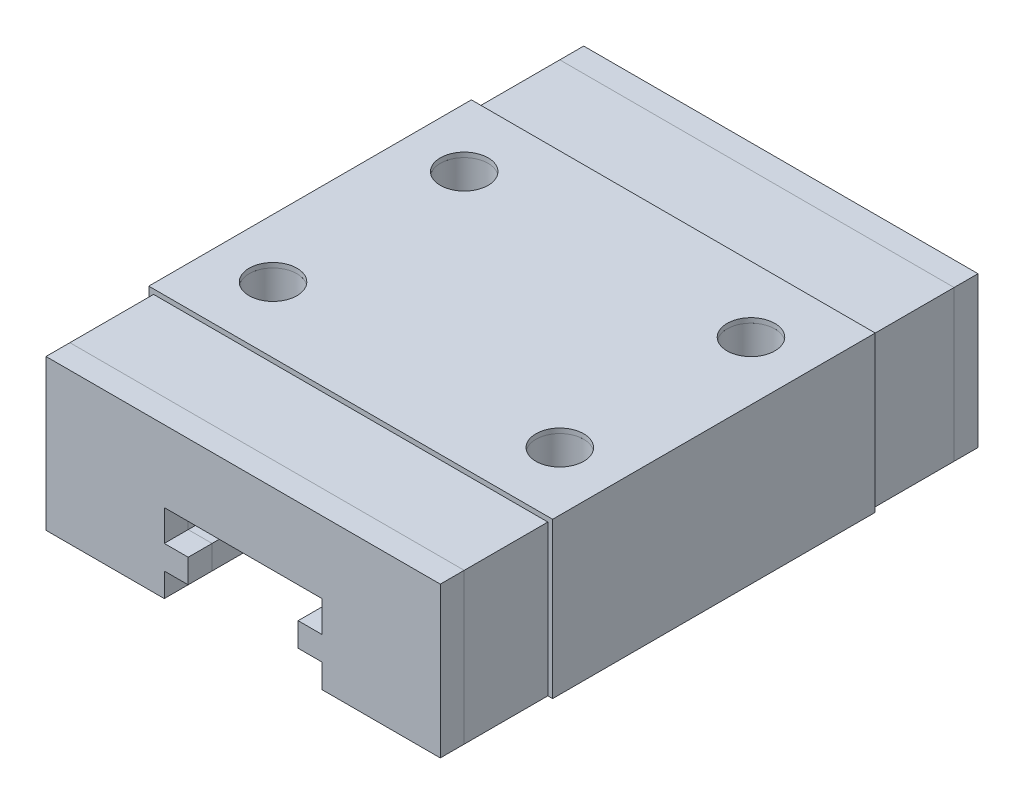
SolidWorks part; units mm, degrees
material "1060 合金"
ref_plane "前视基准面" through (0, 0, 0) normal (0, 0, 1) x (1, 0, 0)
ref_plane "上视基准面" through (0, 0, 0) normal (0, 1, 0) x (1, 0, 0)
ref_plane "右视基准面" through (0, 0, 0) normal (1, 0, 0) x (0, 0, -1)
sketch "草图1" plane through (0, 0, 0) normal (0, 0, 1) x (1, 0, 0)
  line L0 (0, 0) -> (0, 6.3)
  line L1 (0, 6.3) -> (16.5, 6.3)
  line L2 (16.5, 6.3) -> (16.5, 0)
  line L3 (16.5, 0) -> (11.55, 0)
  line L4 (0, 0) -> (4.95, 0)
  line L5 (4.95, 0) -> (4.95, 1)
  line L6 (4.95, 1) -> (5.95, 1)
  line L7 (5.95, 1) -> (5.95, 2)
  line L8 (5.95, 2) -> (4.95, 2)
  line L9 (4.95, 2) -> (4.95, 3.3)
  line L10 (4.95, 3.3) -> (11.55, 3.3)
  line L11 (11.55, 3.3) -> (11.55, 2)
  line L12 (11.55, 2) -> (10.55, 2)
  line L13 (10.55, 2) -> (10.55, 1)
  line L14 (10.55, 1) -> (11.55, 1)
  line L15 (11.55, 1) -> (11.55, 0)
  line L16 (8.25, 6.3) -> (8.25, 0) construction
  dimension "D1" = 16.5
  dimension "D2" = 6.3
  dimension "D3" = 6.6
  dimension "D4" = 3
  dimension "D5" = 1.3
  dimension "D6" = 1
  dimension "D7" = 1
extrude "凸台-拉伸1" add sketch "草图1" along normal blind 1
sketch "草图2" plane through (0, 0, 1) normal (0, 0, 1) x (1, 0, 0)
  line L0 (4.95, 0) -> (4.95, 1)
  line L1 (4.95, 1) -> (5.95, 1)
  line L2 (5.95, 1) -> (5.95, 2)
  line L3 (5.95, 2) -> (4.95, 2)
  line L4 (4.95, 2) -> (4.95, 3.3)
  line L5 (4.95, 3.3) -> (11.55, 3.3)
  line L6 (11.55, 3.3) -> (11.55, 2)
  line L7 (11.55, 2) -> (10.55, 2)
  line L8 (10.55, 2) -> (10.55, 1)
  line L9 (10.55, 1) -> (11.55, 1)
  line L10 (11.55, 1) -> (11.55, 0)
  line L11 (11.55, 0) -> (16.5, 0)
  line L13 (16.5, 0) -> (16.5, 6.3)
  line L14 (16.5, 6.3) -> (0, 6.3)
  line L15 (0, 6.3) -> (0, 0)
  line L16 (0, 0) -> (4.95, 0) construction
  line L17 (0, 0) -> (4.95, 0)
extrude "凸台-拉伸2" add sketch "草图2" along normal blind 20.5 separate body
sketch "草图3" plane through (0, 0, 21.5) normal (0, 0, 1) x (1, 0, 0)
  line L17 (0, 0) -> (4.95, 0)
  line L18 (4.95, 0) -> (4.95, 1)
  line L19 (4.95, 1) -> (5.95, 1)
  line L20 (5.95, 1) -> (5.95, 2)
  line L21 (5.95, 2) -> (4.95, 2)
  line L22 (4.95, 2) -> (4.95, 3.3)
  line L23 (4.95, 3.3) -> (11.55, 3.3)
  line L24 (11.55, 3.3) -> (11.55, 2)
  line L25 (11.55, 2) -> (10.55, 2)
  line L26 (10.55, 2) -> (10.55, 1)
  line L27 (10.55, 1) -> (11.55, 1)
  line L28 (11.55, 1) -> (11.55, 0)
  line L29 (11.55, 0) -> (16.5, 0)
  line L30 (16.5, 0) -> (16.5, 6.3)
  line L31 (16.5, 6.3) -> (0, 6.3)
  line L32 (0, 6.3) -> (0, 0)
  line L33 (0, 0) -> (4.95, 0)
  line L34 (4.95, 0) -> (4.95, 1)
  line L35 (4.95, 1) -> (5.95, 1)
  line L36 (5.95, 1) -> (5.95, 2)
  line L37 (5.95, 2) -> (4.95, 2)
  line L38 (4.95, 2) -> (4.95, 3.3)
  line L39 (4.95, 3.3) -> (11.55, 3.3)
  line L40 (11.55, 3.3) -> (11.55, 2)
  line L41 (11.55, 2) -> (10.55, 2)
  line L42 (10.55, 2) -> (10.55, 1)
  line L43 (10.55, 1) -> (11.55, 1)
  line L44 (11.55, 1) -> (11.55, 0)
  line L45 (11.55, 0) -> (16.5, 0)
  line L46 (16.5, 0) -> (16.5, 6.3)
  line L47 (16.5, 6.3) -> (0, 6.3)
  line L48 (0, 6.3) -> (0, 0)
  dimension "D1" = 0
extrude "凸台-拉伸3" add sketch "草图3" along normal blind 1
ref_plane "基准面1" through (0, 0, 4.5) normal (0, 0, 1) x (1, 0, 0)
fillet "圆角1" radius 0.25 12 edges at (4.95, 0, 0.5) (11.55, 0, 0.5) (11.55, 3.3, 0.5) (4.95, 3.3, 0.5) (4.95, 2, 0.5) (5.95, 2, 0.5) (5.95, 1, 0.5) (4.95, 1, 0.5) (11.55, 1, 0.5) (11.55, 2, 0.5) (10.55, 1, 0.5) (10.55, 2, 0.5)
sketch "草图4" plane through (0, 0, 4.5) normal (0, 0, 1) x (1, 0, 0)
  line L0 (8.25, 6.3) -> (8.25, 3.3) construction
  line L1 (0, 0) -> (-0.2, 0)
  line L2 (-0.2, 0) -> (-0.2, 6.5)
  line L3 (-0.2, 6.5) -> (8.25, 6.5)
  line L4 (8.25, 6.5) -> (8.25, 6.3)
  line L5 (8.25, 6.3) -> (0, 6.3)
  line L6 (0, 6.3) -> (0, 0)
  line L7 (16.5, 6.3) -> (0, 6.3) construction
  line L8 (4.95, 3.3) -> (11.55, 3.3) construction
  line L9 (0, 6.3) -> (0, 0) construction
  line L10 (16.5, 6.3) -> (16.5, 0)
  line L11 (8.25, 6.3) -> (16.5, 6.3)
  line L12 (8.25, 6.5) -> (8.25, 6.3)
  line L13 (16.7, 6.5) -> (8.25, 6.5)
  line L14 (16.7, 0) -> (16.7, 6.5)
  line L15 (16.5, 0) -> (16.7, 0)
  dimension "D1" = 0.2
  dimension "D2" = 0.2
extrude "凸台-拉伸4" add sketch "草图4" along normal blind 13.5 contours L10 L15 L14 L13 L4 L11
sketch "草图5" plane through (0, 6.5, 0) normal (0, 1, 0) x (1, 0, 0)
  line L0 (-0.2, -11.25) -> (16.7, -11.25) construction
  line L1 (-0.2, -18) -> (-0.2, -4.5) construction
  line L3 (8.25, -4.5) -> (8.25, -18) construction
  line L6 (16.7, -18) -> (16.7, -4.5) construction
  line L7 (16.7, -4.5) -> (-0.2, -4.5) construction
  line L8 (16.7, -18) -> (-0.2, -18) construction
  circle A0 centre (2.25, -7.25) radius 1
  circle A1 centre (2.25, -15.25) radius 1
  circle A2 centre (14.25, -15.25) radius 1
  circle A3 centre (14.25, -7.25) radius 1
  dimension "D2" = 12
  dimension "D1" = 2
  dimension "D3" = 8
extrude "切除-拉伸1" cut sketch "草图5" against normal blind 4 contours A1 | A2 | A3 | A0
ref_plane "基准面2" through (8.25, 0, 0) normal (1, 0, 0) x (0, 0, -1)
